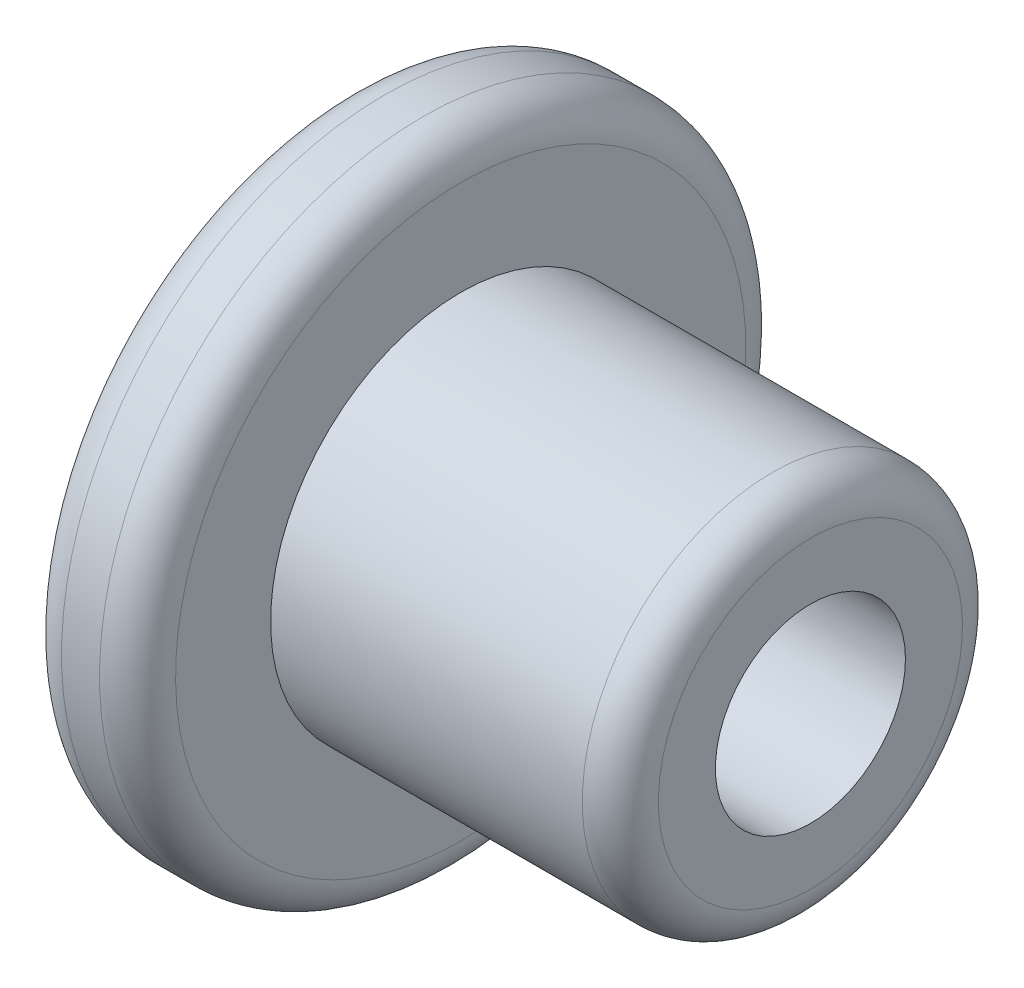
SolidWorks part; units mm, degrees
ref_plane "前视基准面" through (0, 0, 0) normal (0, 0, 1) x (1, 0, 0)
ref_plane "上视基准面" through (0, 0, 0) normal (0, 1, 0) x (1, 0, 0)
ref_plane "右视基准面" through (0, 0, 0) normal (1, 0, 0) x (0, 0, -1)
other "Configuration Table"
sketch "草图1" plane through (0, 0, 0) normal (0, 0, 1) x (1, 0, 0)
  line L0 (0, 0) -> (-1.5, 0)
  line L1 (-1.5, 0) -> (-1.5, 4.25)
  line L2 (-1.5, 4.25) -> (0, 4.25)
  line L3 (0, 4.25) -> (0, 0)
  line L4 (0, 0) -> (0, 2.5)
  line L5 (0, 2.5) -> (4.6, 2.5)
  line L6 (4.6, 2.5) -> (4.6, 0)
  line L7 (4.6, 0) -> (0, 0)
  dimension "D1" = 1.5
  dimension "D2" = 4.25
  dimension "D3" = 4.6
  dimension "D4" = 2.5
revolve "旋转1" add sketch "草图1" angle 360 about L0
fillet "圆角1" radius 0.5 3 edges at (4.6, 2.5, 0) (0, 4.25, 0) (-1.5, 4.25, 0)
hole_wizard "M3 螺纹孔1" positions "草图2" profile "草图3" tap size "M3" standard "GB"
sketch "草图2" plane through (4.6, 0, 0) normal (1, 0, 0) x (0, 0, -1)
  point P0 (0, 0)
sketch "草图3" plane through (4.6, 0, 0) normal (0, 1, 0) x (0, 0, -1)
  line L0 (0, 0) -> (0, 4.7511)
  line L1 (0, 4.7511) -> (1.25, 4)
  line L2 (1.25, 4) -> (1.25, 0)
  line L5 (1.25, 0) -> (0, 0)
  line L10 (0, 4.7511) -> (-1.25, 4) construction
  line L11 (0, -6.35) -> (0, 107.95) construction
  dimension "螺纹孔钻头直径" = 2.5
  dimension "螺纹孔钻头深度" = 4
  dimension "导头角度" = 118
